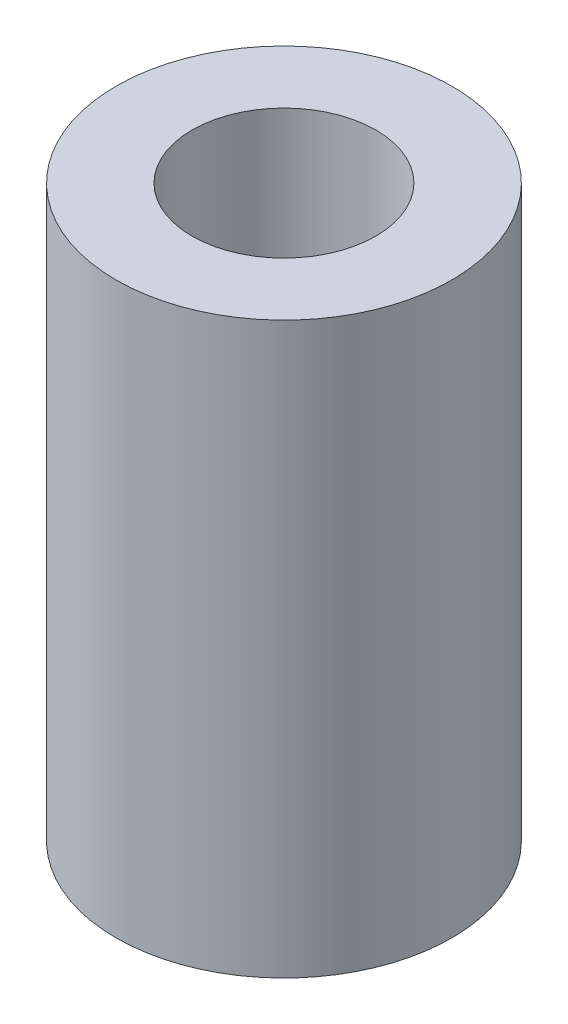
SolidWorks part; units mm, degrees
ref_plane "Front Plane" through (0, 0, 0) normal (0, 0, 1) x (1, 0, 0)
ref_plane "Top Plane" through (0, 0, 0) normal (0, 1, 0) x (1, 0, 0)
ref_plane "Right Plane" through (0, 0, 0) normal (1, 0, 0) x (0, 0, -1)
sketch "Sketch1" plane through (0, 0, 0) normal (0, 1, 0) x (1, 0, 0)
  circle A0 centre (0, 0) radius 44.2
  circle A1 centre (0, 0) radius 24.2
  dimension "D1" = 88.4
  dimension "D2" = 20
extrude "Boss-Extrude1" add sketch "Sketch1" along normal mid plane 150
